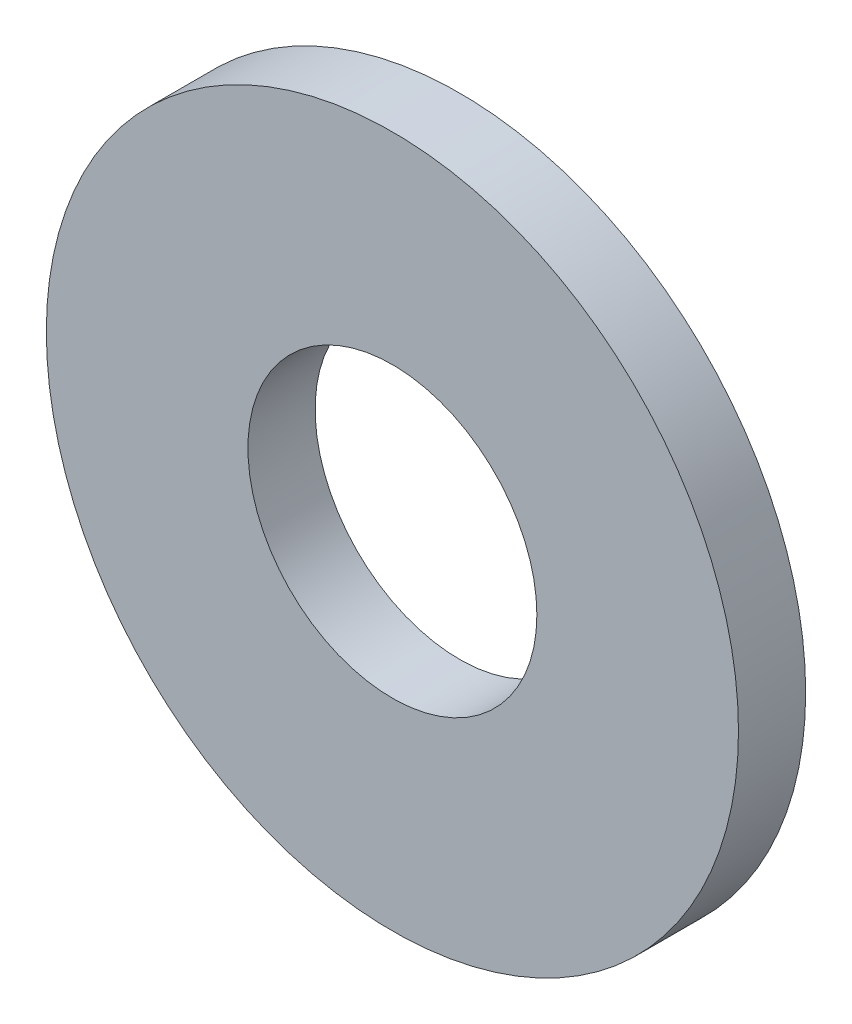
SolidWorks part; units mm, degrees
ref_plane "Plano frontal" through (0, 0, 0) normal (0, 0, 1) x (1, 0, 0)
ref_plane "Plano superior" through (0, 0, 0) normal (0, 1, 0) x (1, 0, 0)
ref_plane "Plano direito" through (0, 0, 0) normal (1, 0, 0) x (0, 0, -1)
sketch "Esboço1" plane through (0, 0, 0) normal (0, 0, 1) x (1, 0, 0)
  circle A0 centre (0, 0) radius 2.15
  circle A1 centre (0, 0) radius 5.15
  dimension "D1" = 10.3
  dimension "D2" = 4.3
extrude "Ressalto-extrusão1" add sketch "Esboço1" along normal blind 1
